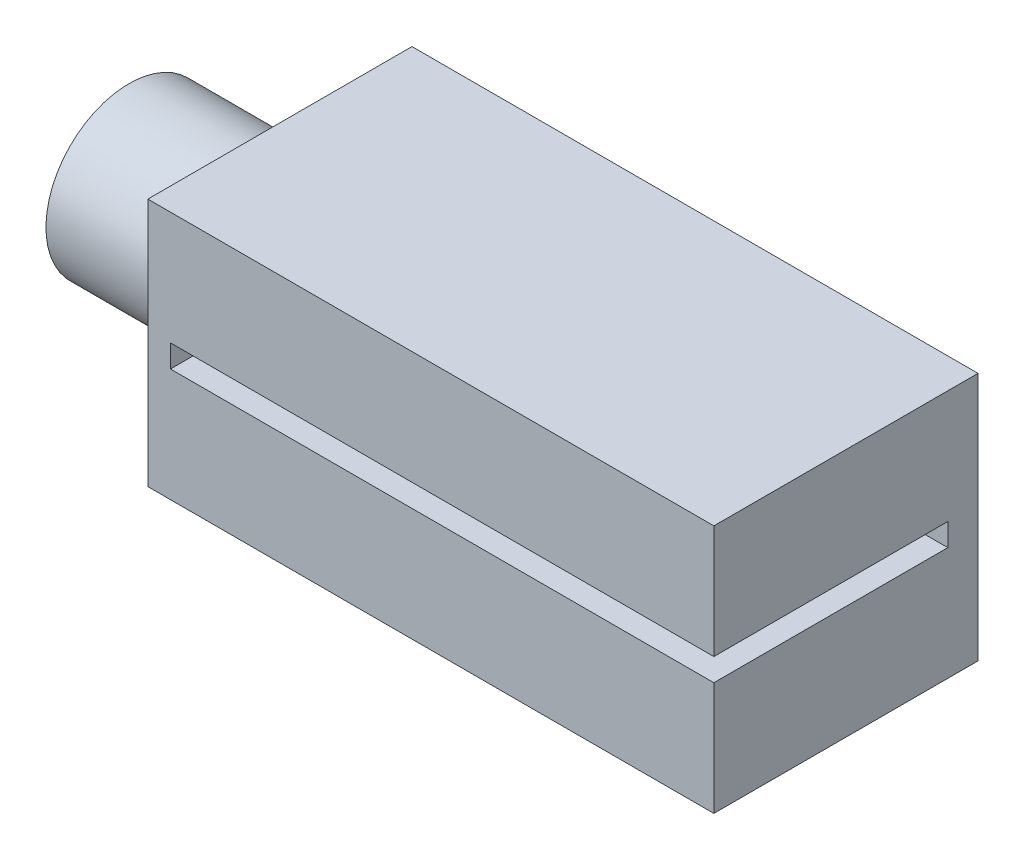
SolidWorks part; units mm, degrees
material "ABS"
ref_plane "Front Plane" through (0, 0, 0) normal (0, 0, 1) x (1, 0, 0)
ref_plane "Top Plane" through (0, 0, 0) normal (0, 1, 0) x (1, 0, 0)
ref_plane "Right Plane" through (0, 0, 0) normal (1, 0, 0) x (0, 0, -1)
sketch "Sketch1" plane through (0, 0, 0) normal (0, 0, 1) x (1, 0, 0)
  line L0 (19.05, 8.382) -> (19.05, 0)
  line L1 (0, 0) -> (19.05, 0)
  line L2 (0, 0) -> (0, 8.382)
  line L3 (0, 8.382) -> (19.05, 8.382)
  point P7 (19.5334, 5.6283)
  dimension "D1" = 8.382
  dimension "D2" = 19.05
extrude "Boss-Extrude2" add sketch "Sketch1" against normal blind 8.89
sketch "Sketch3" plane through (0, 0, 0) normal (0, 0, 1) x (1, 0, 0)
  line L0 (19.05, 4.191) -> (0, 4.191) construction
  line L1 (19.05, 0) -> (19.05, 8.382) construction
  line L2 (0, 8.382) -> (0, 0) construction
  line L3 (0.762, 3.81) -> (19.05, 3.81)
  line L4 (0.762, 3.81) -> (0.762, 4.572)
  line L5 (0.762, 4.572) -> (19.05, 4.572)
  line L6 (19.05, 3.81) -> (19.05, 4.572)
  line L7 (0.762, 3.81) -> (19.05, 4.572) construction
  line L8 (0.762, 4.572) -> (19.05, 3.81) construction
  point P4 (9.906, 4.191)
  dimension "D1" = 18.288
  dimension "D2" = 0.762
extrude "Cut-Extrude1" cut sketch "Sketch3" against normal blind 7.874
sketch "Sketch4" plane through (0, 0, 0) normal (-1, 0, 0) x (0, 0, 1)
  line L1 (-4.445, 8.382) -> (-4.445, 0) construction
  line L2 (0, 4.191) -> (-8.89, 4.191) construction
  line L3 (0, 8.382) -> (0, 0) construction
  line L4 (-8.89, 8.382) -> (0, 8.382) construction
  line L5 (-8.89, 0) -> (0, 0) construction
  circle A0 centre (-4.445, 4.191) radius 2.794
  dimension "D2" = 5.588
extrude "Boss-Extrude3" add sketch "Sketch4" along normal blind 5.08
